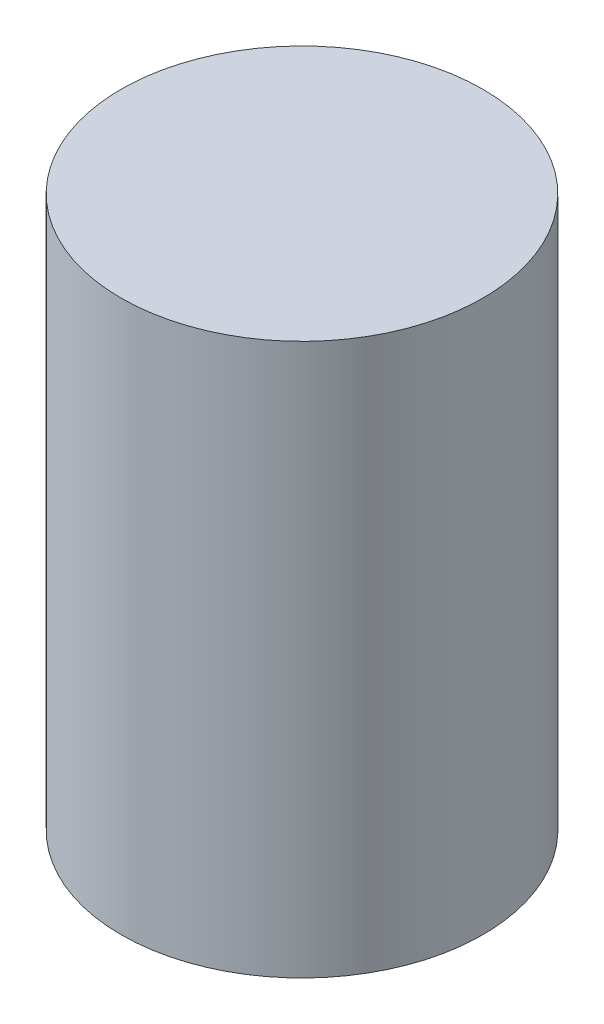
SolidWorks part; units mm, degrees
ref_plane "Front Plane" through (0, 0, 0) normal (0, 0, 1) x (1, 0, 0)
ref_plane "Top Plane" through (0, 0, 0) normal (0, 1, 0) x (1, 0, 0)
ref_plane "Right Plane" through (0, 0, 0) normal (1, 0, 0) x (0, 0, -1)
sketch "Sketch1" plane through (0, 0, 0) normal (0, 1, 0) x (1, 0, 0)
  circle A0 centre (0, 0) radius 6.25
  dimension "D1" = 12.5
extrude "Boss-Extrude1" add sketch "Sketch1" along normal blind 19.05 contours A0
